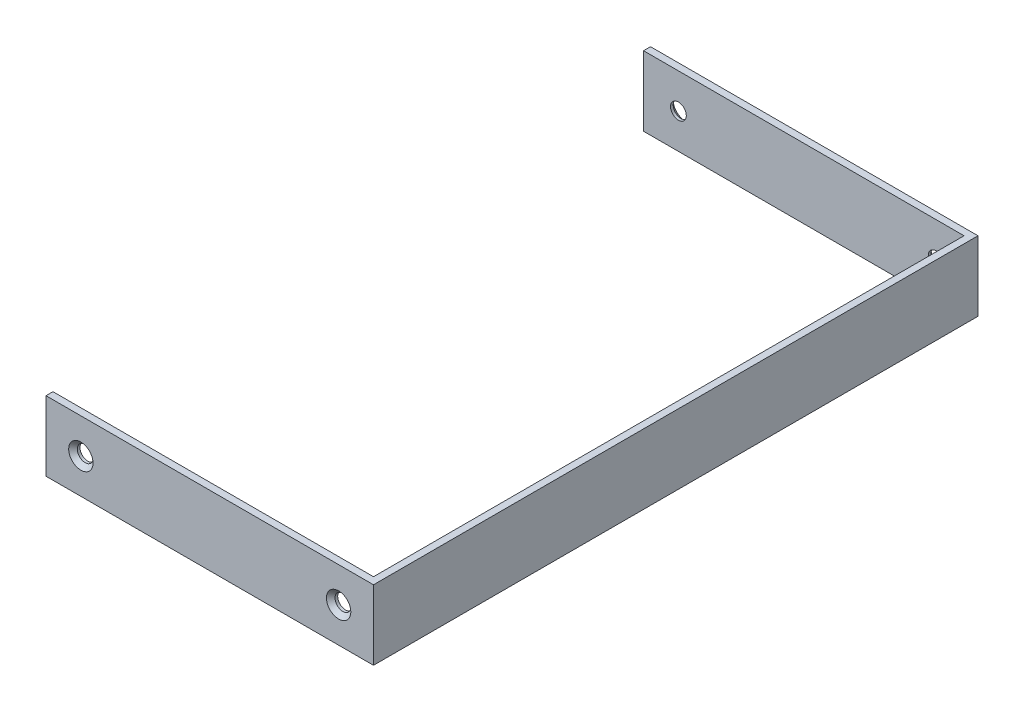
SolidWorks part; units mm, degrees
ref_plane "Front Plane" through (0, 0, 0) normal (0, 0, 1) x (1, 0, 0)
ref_plane "Top Plane" through (0, 0, 0) normal (0, 1, 0) x (1, 0, 0)
ref_plane "Right Plane" through (0, 0, 0) normal (1, 0, 0) x (0, 0, -1)
sketch "Sketch3" plane through (0, 0, 0) normal (0, 0, 1) x (1, 0, 0)
  line L1 (44.7153, 9.525) -> (-44.7153, 9.525)
  line L2 (44.7153, 9.525) -> (44.7153, -9.525)
  line L3 (44.7153, -9.525) -> (-44.7153, -9.525)
  line L4 (-44.7153, 9.525) -> (-44.7153, -9.525)
  point P1 (44.7153, 0)
  point P4 (0, 9.525)
  dimension "D1" = 89.4307
  dimension "D2" = 19.05
extrude "Boss-Extrude1" add sketch "Sketch3" along normal mid plane 165.0767
sketch "Sketch4" plane through (0, -9.525, 0) normal (0, -1, 0) x (1, 0, 0)
  line L1 (-44.7153, 80.6333) -> (42.8103, 80.6333)
  line L2 (-44.7153, 80.6333) -> (-44.7153, -80.6333)
  line L3 (-44.7153, -80.6333) -> (42.8103, -80.6333)
  line L4 (42.8103, 80.6333) -> (42.8103, -80.6333)
  line L5 (-44.7153, 82.5383) -> (44.7153, 82.5383) construction
  line L6 (44.7153, 82.5383) -> (44.7153, -82.5383) construction
  line L7 (-44.7153, 82.5383) -> (-44.7153, -82.5383) construction
  point P6 (42.8103, 0)
  dimension "D1" = 1.905
  dimension "D2" = 1.905
extrude "Cut-Extrude1" cut sketch "Sketch4" against normal through all
sketch "Sketch5" plane through (0, 0, -82.5383) normal (0, 0, -1) x (-1, 0, 0)
  line L2 (35.1903, 0) -> (35.1903, -9.525) construction
  line L3 (44.7153, -9.525) -> (-44.7153, -9.525) construction
  line L13 (-35.1903, 0) -> (-35.1903, -9.525) construction
  line L15 (-35.1903, 0) -> (-44.7153, 0) construction
  line L17 (-44.7153, -9.525) -> (-44.7153, 9.525) construction
  line L18 (35.1903, 0) -> (44.7153, 0) construction
  line L19 (44.7153, 9.525) -> (44.7153, -9.525) construction
  point P9 (35.1903, 0)
  point P48 (-35.1903, 0)
hole_wizard "#6 Clearance Hole1" positions "Sketch5" profile "Sketch6" hole size "#6" standard "ANSI Inch" end condition up to next
sketch "Sketch6" plane through (35.1903, 0, -82.5383) normal (1, 0, 0) x (0, 1, 0)
  line L0 (0, 0) -> (0, 1.905)
  line L1 (0, 1.905) -> (2.1526, 1.905)
  line L2 (2.1526, 1.905) -> (2.1526, 1.1747)
  line L3 (2.1526, 1.1747) -> (3.3274, 0)
  line L5 (3.3274, 0) -> (0, 0)
  line L6 (-2.1526, 1.1747) -> (-3.3274, 0) construction
  line L11 (0, -6.35) -> (0, 107.95) construction
  dimension "Thru Hole Dia." = 4.3053
  dimension "Thru Hole Depth" = 1.905
  dimension "Near C'Sink Dia." = 6.6548
  dimension "Near C'Sink Angle" = 90
sketch "Sketch7" plane through (0, 0, 82.5383) normal (0, 0, 1) x (1, 0, 0)
  circle A0 centre (35.1903, 0) radius 2.1526 construction
  circle A1 centre (-35.1903, 0) radius 2.1526 construction
  point P0 (-35.1903, 0)
  point P1 (35.1903, 0)
hole_wizard "#6 Clearance Hole2" positions "Sketch7" profile "Sketch8" hole size "#6" standard "ANSI Inch"
sketch "Sketch8" plane through (-35.1903, 0, 82.5383) normal (1, 0, 0) x (0, -1, 0)
  line L0 (0, 0) -> (0, 8.1514)
  line L1 (0, 8.1514) -> (2.1526, 6.858)
  line L2 (2.1526, 6.858) -> (2.1526, 1.1748)
  line L3 (2.1526, 1.1748) -> (3.3274, 0)
  line L5 (3.3274, 0) -> (0, 0)
  line L6 (-2.1526, 1.1747) -> (-3.3274, 0) construction
  line L10 (0, 8.1514) -> (-2.1527, 6.858) construction
  line L11 (0, -6.35) -> (0, 107.95) construction
  dimension "Hole Dia." = 4.3053
  dimension "Hole Depth" = 6.858
  dimension "Near C'Sink Dia." = 6.6548
  dimension "Near C'Sink Angle" = 90
  dimension "Drill Angle" = 118
